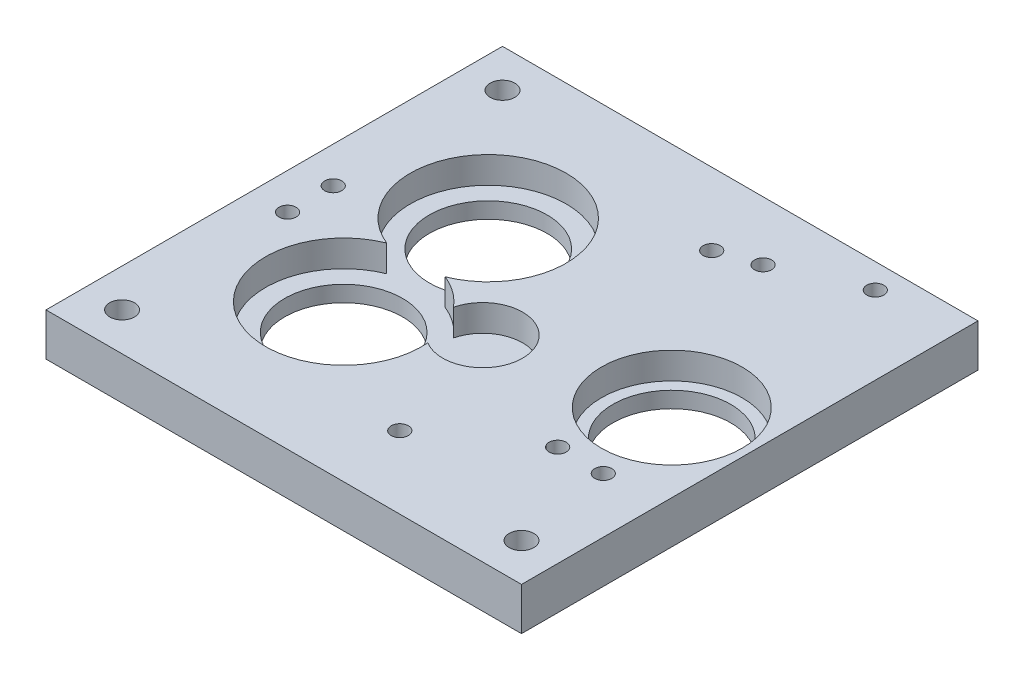
SolidWorks part; units mm, degrees
ref_plane "Front" through (0, 0, 0) normal (0, 0, 1) x (1, 0, 0)
ref_plane "Top" through (0, 0, 0) normal (0, 1, 0) x (1, 0, 0)
ref_plane "Right" through (0, 0, 0) normal (1, 0, 0) x (0, 0, -1)
sketch "Sketch1" plane through (0, 0, 0) normal (0, 1, 0) x (1, 0, 0)
  line L1 (-62.5, -60) -> (62.5, -60)
  line L2 (-62.5, -60) -> (-62.5, 60)
  line L3 (-62.5, 60) -> (62.5, 60)
  line L4 (62.5, -60) -> (62.5, 60)
  line L5 (-62.5, -60) -> (62.5, 60) construction
  line L6 (-62.5, 60) -> (62.5, -60) construction
  point P0 (0, 0)
  dimension "D1" = 125
  dimension "D2" = 120
extrude "Test_Base_Postion" add sketch "Sketch1" along normal blind 11.215
sketch "Fingers_Position" plane through (0, 11.215, 0) normal (0, 1, 0) x (1, 0, 0)
  line L0 (-62.5, 0) -> (62.5, 0) construction
  line L1 (-62.5, 60) -> (-62.5, -60) construction
  line L2 (62.5, -60) -> (62.5, 60) construction
  line L3 (-11.5, 35) -> (-11.5, 3) construction
  line L4 (-39, 35) -> (16, 35) construction
  line L5 (-39, 35) -> (-39, 3) construction
  line L6 (-39, 3) -> (16, 3) construction
  line L7 (16, 35) -> (16, 3) construction
  line L8 (16, -35) -> (-39, -35) construction
  line L9 (16, -35) -> (16, -3) construction
  line L10 (16, -3) -> (-39, -3) construction
  line L11 (-39, -35) -> (-39, -3) construction
  line L12 (-11.5, 19) -> (-39, 19) construction
  line L13 (-11.5, -3) -> (-11.5, -35) construction
  line L14 (-39, -19) -> (-11.5, -19) construction
  line L15 (-39, -19) -> (-45.25, -19) construction
  line L16 (26, 49) -> (26, -6) construction
  line L17 (26, -6) -> (58, -6) construction
  line L18 (58, -6) -> (58, 49) construction
  line L19 (58, 49) -> (26, 49) construction
  line L20 (30, 9) -> (30, -27) construction
  line L21 (30, -27) -> (54, -27) construction
  line L22 (54, -27) -> (54, 9) construction
  line L23 (54, 9) -> (30, 9) construction
  line L24 (30, -9) -> (54, -9) construction
  line L25 (42, 49) -> (42, -6) construction
  circle A0 centre (-25.25, -19) radius 20 construction
  circle A1 centre (-25.25, -19) radius 20.5 construction
  circle A2 centre (-25.25, 19) radius 20 construction
  circle A3 centre (-25.25, 19) radius 20.5 construction
  circle A4 centre (-25.25, 19) radius 19 construction
  circle A5 centre (-25.25, -19) radius 19 construction
  circle A6 centre (42, 0) radius 17.75 construction
  circle A7 centre (42, 0) radius 9 construction
  point P50 (42, 9)
  dimension "D1" = 40
  dimension "D2" = 41
  dimension "D8" = 38
  dimension "D7" = 18
  dimension "D9" = 35.5
  dimension "D3" = 55
  dimension "D4" = 32
  dimension "D5" = 55
  dimension "D6" = 32
  dimension "D10" = 24
  dimension "D11" = 32
  dimension "D12" = 55
  dimension "D13" = 40
  dimension "D14" = 20.5
  dimension "D15" = 10
sketch "Thumb_Position" plane through (0, 11.215, 0) normal (0, 1, 0) x (1, 0, 0)
  line L0 (42, 49) -> (42, -6) construction
  line L1 (58, -6) -> (26, -6) construction
  line L2 (58, -6) -> (58, 49) construction
  line L3 (58, 49) -> (26, 49) construction
  line L4 (26, -6) -> (26, 49) construction
  line L5 (30, -9) -> (54, -9) construction
  line L6 (54, -27) -> (30, -27) construction
  line L7 (54, -27) -> (54, 9) construction
  line L8 (54, 9) -> (30, 9) construction
  line L9 (30, -27) -> (30, 9) construction
  line L10 (42, 9) -> (42, -9) construction
  line L11 (62.5, -60) -> (62.5, 60) construction
  line L12 (-62.5, 0) -> (62.5, 0) construction
  circle A0 centre (42, 0) radius 17.75 construction
  circle A1 centre (42, 0) radius 9 construction
  dimension "D1" = 18
  dimension "D2" = 35.5
  dimension "D3" = 24
  dimension "D4" = 36
  dimension "D5" = 55
  dimension "D6" = 32
  dimension "D7" = 20.5
  dimension "D8" = 40
sketch "Intermediate_Gear_Position" plane through (0, 11.215, 0) normal (0, 1, 0) x (1, 0, 0)
  line L0 (-38, -12) -> (-38, 12) construction
  line L1 (-20, 12) -> (-20, -12) construction
  line L2 (-20, 12) -> (-56, 12) construction
  line L3 (-56, 12) -> (-56, -12) construction
  line L4 (-20, -12) -> (-56, -12) construction
  line L5 (-38, 0) -> (-20, 0) construction
  line L7 (-62.5, 0) -> (62.5, 0) construction
  line L10 (16, 35) -> (16, 3) construction
  circle A3 centre (0.6461, -8.3515) radius 18 construction
  circle A6 centre (-29, 0) radius 12.8 construction
  circle A7 centre (0.6461, -8.3515) radius 9 construction
  circle A8 centre (-25.25, -19) radius 19 construction
  dimension "D3" = 36
  dimension "D6" = 36
  dimension "D10" = 18
  dimension "D11" = 25.6
  dimension "D1" = 24
  dimension "D2" = 36
sketch "Sketch8" plane through (0, 11.215, 0) normal (0, 1, 0) x (1, 0, 0)
  circle A0 centre (-25.25, 19) radius 20.5
  circle A1 centre (-25.25, -19) radius 20.5
  dimension "D1" = 41
extrude "Finger_Gears" cut sketch "Sketch8" against normal blind 7 contours A1 A0 | A0 A1 | A0 A1
sketch "Sketch9" plane through (0, 11.215, 0) normal (0, 1, 0) x (1, 0, 0)
  circle A0 centre (0.6461, -8.3515) radius 10.5
  dimension "D1" = 21
extrude "Intermediate_Gear" cut sketch "Sketch9" against normal blind 7
sketch "Sketch11" plane through (0, 11.215, 0) normal (0, 1, 0) x (1, 0, 0)
  circle A0 centre (42, 0) radius 18.5
  dimension "D1" = 37
extrude "XL320_Finger_Knuckle_Mount" cut sketch "Sketch11" against normal blind 7
sketch "Sketch10" plane through (0, 11.215, 0) normal (0, 1, 0) x (1, 0, 0)
  circle A0 centre (-25.25, 19) radius 15.5
  circle A1 centre (-25.25, -19) radius 15.5
  circle A2 centre (42, 0) radius 15.5
  dimension "D1" = 31
extrude "Connect_Finger_Holes" cut sketch "Sketch10" against normal through all
sketch "Thumb_Mount_Holes" plane through (0, 11.215, 0) normal (0, 1, 0) x (1, 0, 0)
  line L0 (42, 49) -> (42, 53.5) construction
  line L1 (58, 49) -> (26, 49) construction
  line L2 (26, 49) -> (21.5, 49) construction
  line L3 (21.5, 49) -> (21.5, 44.5) construction
  line L4 (42, -27) -> (42, -9) construction
  line L5 (54, -27) -> (30, -27) construction
  line L6 (48, -27) -> (48, -24) construction
  line L7 (48, -24) -> (54, -24) construction
  line L8 (54, -27) -> (54, 9) construction
  circle A0 centre (21.5, 44.5) radius 2.25
  circle A1 centre (42, 53.5) radius 2.25
  circle A2 centre (48, -24) radius 2.25
  circle A3 centre (36, -24) radius 2.25
  dimension "D3" = 4.5
  dimension "D5" = 4.5
  dimension "D1" = 6
  dimension "D2" = 3
  dimension "D4" = 4.5
extrude "Thumb_Mount_Holes_(M4)" cut sketch "Thumb_Mount_Holes" against normal through all
sketch "Sketch16" plane through (0, 11.215, 0) normal (0, 1, 0) x (1, 0, 0)
  line L0 (-62.5, 0) -> (62.5, 0) construction
  line L1 (-62.5, 60) -> (-62.5, -60) construction
  line L2 (16, 35) -> (16, 41) construction
  line L3 (16, 41) -> (11.5, 41) construction
  line L4 (-53, 12) -> (-53, 6) construction
  line L5 (-20, 12) -> (-56, 12) construction
  line L6 (-53, 6) -> (-56, 6) construction
  line L7 (-56, 12) -> (-56, -12) construction
  circle A0 centre (11.5, 41) radius 2.25
  circle A1 centre (11.5, -41) radius 2.25
  circle A2 centre (-53, 6) radius 2.25
  circle A4 centre (-53, -6) radius 2.25
  dimension "D2" = 4.5
  dimension "D4" = 4.5
  dimension "D1" = 6
  dimension "D3" = 4.5
  dimension "D5" = 6
  dimension "D6" = 3
extrude "Fingers_Mount_Holes_(M4)" cut sketch "Sketch16" against normal through all
sketch "Sketch17" plane through (0, 11.215, 0) normal (0, 1, 0) x (1, 0, 0)
  line L0 (-62.5, 50) -> (-52.5, 50) construction
  line L1 (-62.5, 60) -> (-62.5, -60) construction
  line L2 (62.5, 60) -> (-62.5, 60) construction
  line L3 (-62.5, 0) -> (62.5, 0) construction
  line L4 (0, 0) -> (0, -60) construction
  line L5 (-62.5, -60) -> (62.5, -60) construction
  circle A0 centre (-52.5, 50) radius 3.25
  circle A1 centre (-52.5, -50) radius 3.25
  circle A2 centre (52.5, -50) radius 3.25
  dimension "D3" = 6.5
  dimension "D1" = 10
  dimension "D2" = 10
extrude "Connect_Holes_(M6)" cut sketch "Sketch17" against normal through all
sketch "Sketch18" plane through (0, 0, 0) normal (0, -1, 0) x (1, 0, 0)
  circle A0 centre (11.5, 41) radius 3.75
  circle A1 centre (11.5, -41) radius 3.75
  circle A2 centre (21.5, -44.5) radius 3.75
  circle A3 centre (42, -53.5) radius 3.75
  dimension "D1" = 7.5
extrude "Nuts_(M4)" cut sketch "Sketch18" against normal blind 4
sketch "Sketch19" plane through (0, 0, 0) normal (0, -1, 0) x (1, 0, 0)
  circle A0 centre (-52.5, 50) radius 5.25
  circle A1 centre (52.5, 50) radius 5.25
  circle A2 centre (-52.5, -50) radius 5.25
  dimension "D1" = 10.5
extrude "Nuts_(M6)" cut sketch "Sketch19" against normal blind 6
